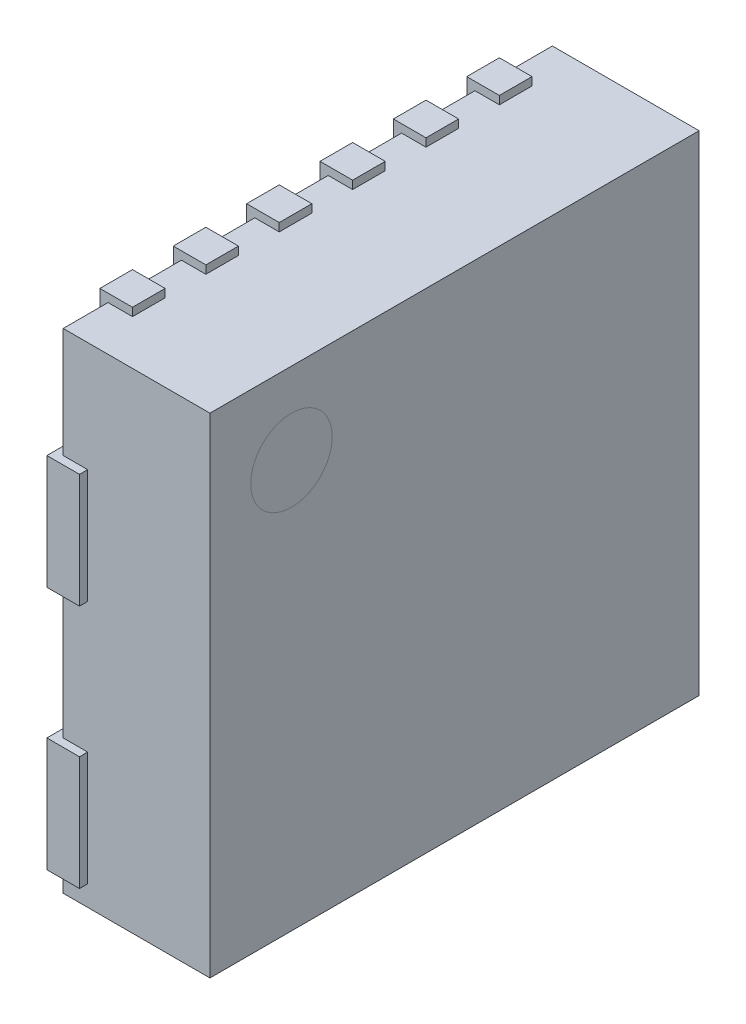
SolidWorks part; units mm, degrees
ref_plane "Front" through (0, 0, 0) normal (0, 0, 1) x (1, 0, 0)
ref_plane "Top" through (0, 0, 0) normal (0, 1, 0) x (1, 0, 0)
ref_plane "Right" through (0, 0, 0) normal (1, 0, 0) x (0, 0, -1)
ref_plane "Плоскость2" through (0.05, 0, 0) normal (1, 0, 0) x (0, 0, -1)
sketch "Эскиз1" plane through (0.05, 0, 0) normal (1, 0, 0) x (0, 0, -1)
  line L1 (-1.5, 1.5) -> (1.5, 1.5)
  line L2 (-1.5, 1.5) -> (-1.5, -1.5)
  line L3 (-1.5, -1.5) -> (1.5, -1.5)
  line L4 (1.5, 1.5) -> (1.5, -1.5)
  dimension "D1" = 3
  dimension "D2" = 3
  dimension "D3" = 1.5
  dimension "D4" = 1.5
extrude "Бобышка-Вытянуть1" add sketch "Эскиз1" along normal blind 0.9
sketch "Эскиз2" plane through (0.95, 0, 0) normal (1, 0, 0) x (0, 0, -1)
  line L0 (1.5, 1.5) -> (-1.5, 1.5) construction
  line L1 (-1.5, 1.5) -> (-1.5, -1.5) construction
  circle A0 centre (-1, 1) radius 0.25
  dimension "D1" = 0.5
  dimension "D2" = 0.5
  dimension "D3" = 0.5
extrude "Вырез-Вытянуть1" cut sketch "Эскиз2" against normal blind 0.1
ref_plane "Плоскость1" through (0.9, 0, 0) normal (1, 0, 0) x (0, 0, -1)
sketch "Эскиз3" plane through (0.9, 0, 0) normal (1, 0, 0) x (0, 0, -1)
  circle A0 centre (-1, 1) radius 0.25
  circle A1 centre (-1, 1) radius 0.25 construction
extrude "Бобышка-Вытянуть2" add sketch "Эскиз3" along normal blind 0.05 separate body contours A0
sketch "Эскиз4" plane through (0.05, 0, 0) normal (-1, 0, 0) x (0, 0, 1)
  line L0 (-1.5, 1.5) -> (1.5, 1.5) construction
  line L1 (-1.025, 1.15) -> (-1.025, 1.55)
  line L2 (-1.025, 1.15) -> (-1.225, 1.15)
  line L3 (-1.225, 1.15) -> (-1.225, 1.55)
  line L4 (-1.025, 1.55) -> (-1.225, 1.55)
  line L5 (-0.575, 1.15) -> (-0.575, 1.55)
  line L6 (-0.575, 1.15) -> (-0.775, 1.15)
  line L7 (-0.775, 1.15) -> (-0.775, 1.55)
  line L8 (-0.575, 1.55) -> (-0.775, 1.55)
  line L9 (-0.125, 1.15) -> (-0.125, 1.55)
  line L10 (-0.125, 1.15) -> (-0.325, 1.15)
  line L11 (-0.325, 1.15) -> (-0.325, 1.55)
  line L12 (-0.125, 1.55) -> (-0.325, 1.55)
  line L13 (0.325, 1.15) -> (0.325, 1.55)
  line L14 (0.325, 1.15) -> (0.125, 1.15)
  line L15 (0.125, 1.15) -> (0.125, 1.55)
  line L16 (0.325, 1.55) -> (0.125, 1.55)
  line L17 (0.775, 1.15) -> (0.775, 1.55)
  line L18 (0.775, 1.15) -> (0.575, 1.15)
  line L19 (0.575, 1.15) -> (0.575, 1.55)
  line L20 (0.775, 1.55) -> (0.575, 1.55)
  line L21 (1.225, 1.15) -> (1.225, 1.55)
  line L22 (1.225, 1.15) -> (1.025, 1.15)
  line L23 (1.025, 1.15) -> (1.025, 1.55)
  line L24 (1.225, 1.55) -> (1.025, 1.55)
  line L25 (1.55, 0.825) -> (-0.25, 0.825)
  line L27 (-0.25, 0.825) -> (-0.25, 0.425)
  line L28 (-0.25, 0.425) -> (0.2, 0.425)
  line L29 (0.2, 0.425) -> (0.5, 0.125)
  line L30 (0.5, 0.125) -> (1.55, 0.125)
  line L31 (1.55, 0.125) -> (1.55, 0.825)
  line L32 (-0.2, 0.15) -> (0.2, 0.15)
  line L33 (0.2, 0.15) -> (0.55, -0.2)
  line L34 (0.55, -0.2) -> (0.55, -0.35)
  line L35 (0.55, -0.35) -> (0.2, -0.7)
  line L36 (0.2, -0.7) -> (-0.2, -0.7)
  line L37 (-0.2, -0.7) -> (-0.55, -0.35)
  line L38 (-0.55, -0.35) -> (-0.55, -0.2)
  line L39 (-0.55, -0.2) -> (-0.2, 0.15)
  line L40 (-0.2, 0.15) -> (0.2, -0.7) construction
  line L41 (-0.2, -0.7) -> (0.2, 0.15) construction
  line L42 (-1.5, -1.5) -> (-1.5, 1.5) construction
  line L43 (-0.55, -0.275) -> (0.55, -0.275) construction
  line L44 (1.55, -0.675) -> (1.55, -1.375)
  line L45 (0.5, -0.675) -> (1.55, -0.675)
  line L46 (0.2, -0.975) -> (0.5, -0.675)
  line L47 (-0.25, -0.975) -> (0.2, -0.975)
  line L48 (-0.25, -1.375) -> (-0.25, -0.975)
  line L49 (1.55, -1.375) -> (-0.25, -1.375)
  line L50 (-1.55, 0.355) -> (-0.55, 0.355)
  line L51 (-1.55, 0.805) -> (-0.55, 0.805)
  line L52 (-1.55, 0.805) -> (-1.55, 0.545)
  line L53 (-1.55, 0.545) -> (-0.55, 0.545)
  line L54 (-0.55, 0.805) -> (-0.55, 0.545)
  line L55 (-1.55, 0.355) -> (-1.55, 0.095)
  line L56 (-0.55, 0.355) -> (-0.55, 0.095)
  line L57 (-1.55, 0.095) -> (-0.55, 0.095)
  line L58 (1.5, 1.5) -> (1.5, -1.5) construction
  line L59 (-1.55, -0.675) -> (-0.55, -0.675)
  line L60 (-1.55, -0.675) -> (-1.55, -1.375)
  line L61 (-1.55, -1.375) -> (-0.55, -1.375)
  line L62 (-0.55, -0.675) -> (-0.55, -1.375)
  point P29 (-0.225, 1.55)
  point P43 (0, -0.275)
  point P55 (1.55, 0.475)
  point P56 (1.55, -1.025)
  point P69 (-1.55, -1.025)
  point P70 (-1.55, 0.225)
  dimension "D1" = 0.2
  dimension "D2" = 0.225
  dimension "D4" = 0.45
  dimension "D5" = 0.4
  dimension "D6" = 1.1
  dimension "D7" = 0.4
  dimension "D8" = 1.5
  dimension "D9" = 1.775
  dimension "D10" = 0.85
  dimension "D11" = 1.8
  dimension "D12" = 0.4
  dimension "D13" = 0.45
  dimension "D14" = 0.7
  dimension "D15" = 1.5
  dimension "D16" = 1
  dimension "D17" = 0.26
  dimension "D19" = 0.45
  dimension "D20" = 1.275
  dimension "D21" = 1.25
  dimension "D22" = 0.7
  dimension "D23" = 0.05
  dimension "D24" = 0.05
  dimension "D25" = 0.05
  dimension "D3" = 6
  dimension "D18" = 2
extrude "Бобышка-Вытянуть3" add sketch "Эскиз4" along normal blind 0.05 and the other way blind 0.15 separate body
